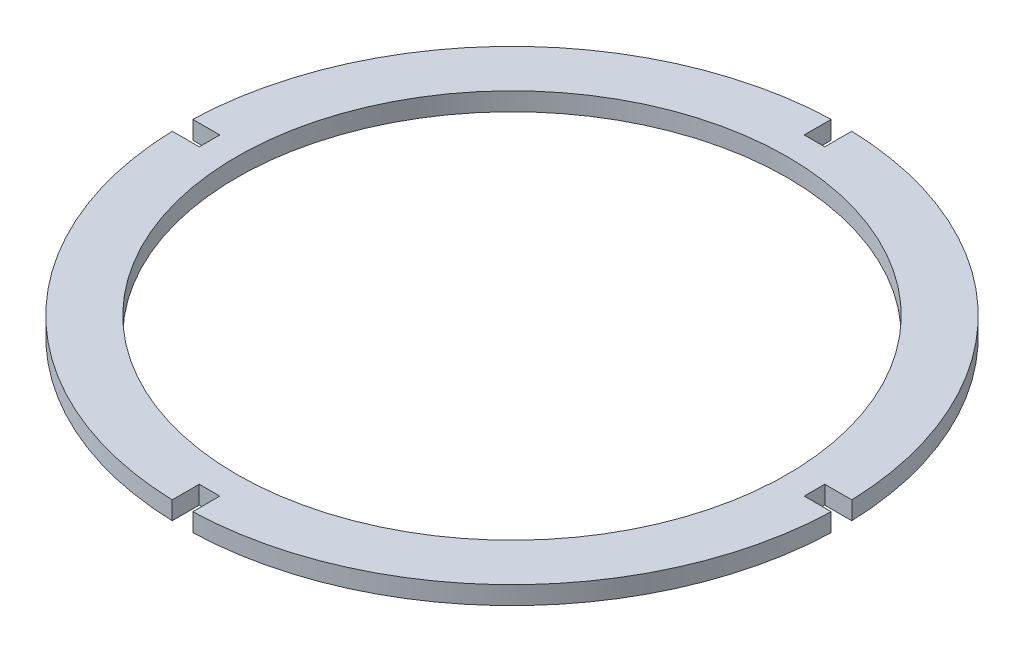
SolidWorks part; units mm, degrees
material "Thornel Mat VMA"
ref_plane "Front Plane" through (0, 0, 0) normal (0, 0, 1) x (1, 0, 0)
ref_plane "Top Plane" through (0, 0, 0) normal (0, 1, 0) x (1, 0, 0)
ref_plane "Right Plane" through (0, 0, 0) normal (1, 0, 0) x (0, 0, -1)
sketch "Sketch1" plane through (0, 0, 0) normal (0, 1, 0) x (1, 0, 0)
  line L0 (-54.5, 0) -> (-45.5, 0) construction
  line L1 (-1.7, 54.4735) -> (1.7, 54.4735) construction
  line L2 (-1.7, 54.4735) -> (-1.7, 50)
  line L3 (-1.7, 50) -> (1.7, 50)
  line L4 (1.7, 54.4735) -> (1.7, 50)
  line L5 (54.4735, 1.7) -> (50, 1.7)
  line L6 (54.4735, 1.7) -> (54.4735, -1.7) construction
  line L7 (54.4735, -1.7) -> (50, -1.7)
  line L8 (50, 1.7) -> (50, -1.7)
  line L9 (-54.4735, 1.7) -> (-50, 1.7)
  line L10 (-54.4735, 1.7) -> (-54.4735, -1.7) construction
  line L11 (-54.4735, -1.7) -> (-50, -1.7)
  line L12 (-50, 1.7) -> (-50, -1.7)
  line L13 (-1.7, -54.4735) -> (1.7, -54.4735) construction
  line L14 (-1.7, -54.4735) -> (-1.7, -50)
  line L15 (-1.7, -50) -> (1.7, -50)
  line L16 (1.7, -54.4735) -> (1.7, -50)
  circle A0 centre (0, 0) radius 45.5
  circle A1 centre (0, 0) radius 54.5 construction
  arc A2 (-54.4735, -1.7) -> (-1.7, -54.4735) centre (0, 0) ccw
  arc A3 (1.7, -54.4735) -> (54.4735, -1.7) centre (0, 0) ccw
  arc A4 (54.4735, 1.7) -> (1.7, 54.4735) centre (0, 0) ccw
  arc A5 (-54.4735, 1.7) -> (-1.7, 54.4735) centre (0, 0) cw
  point P7 (-1.7, 54.4735)
  point P20 (-50, 0)
  point P24 (0, 50)
  point P25 (0, -50)
  point P26 (-50, 0)
  point P27 (50, 0)
  point P31 (0, 0)
  dimension "D1" = 91
  dimension "D2" = 109
  dimension "D3" = 3.4
extrude "Boss-Extrude1" add sketch "Sketch1" along normal mid plane 3
